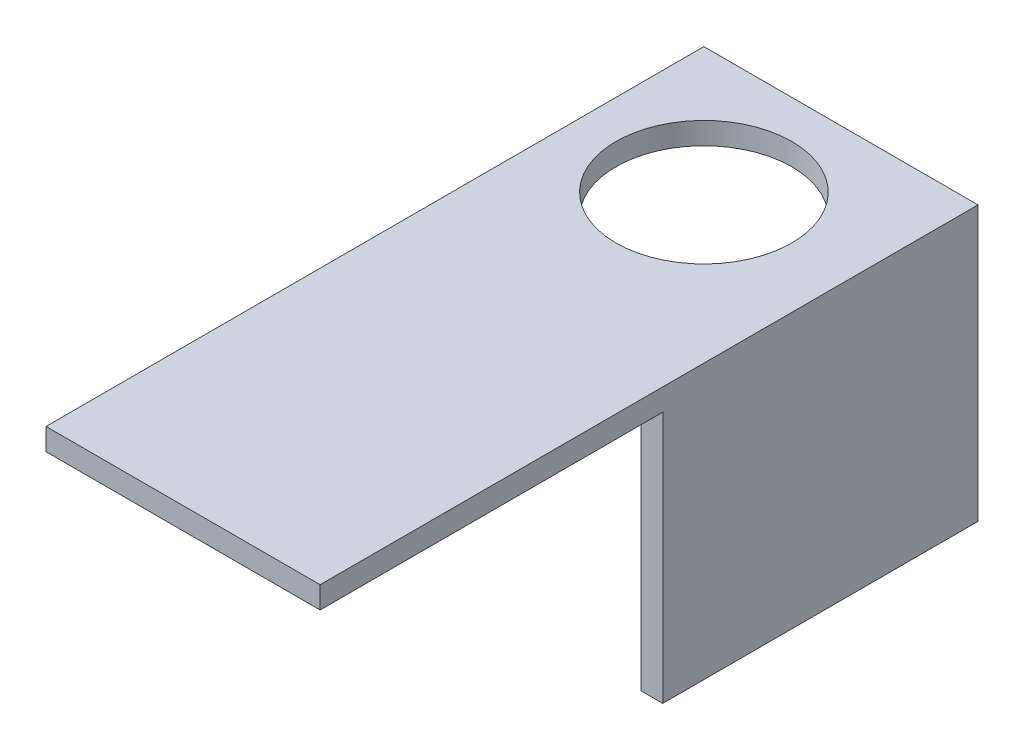
SolidWorks part; units mm, degrees
ref_plane "Alzado" through (0, 0, 0) normal (0, 0, 1) x (1, 0, 0)
ref_plane "Planta" through (0, 0, 0) normal (0, 1, 0) x (1, 0, 0)
ref_plane "Vista lateral" through (0, 0, 0) normal (1, 0, 0) x (0, 0, -1)
sketch "Croquis1" plane through (0, 0, 0) normal (0, 0, 1) x (1, 0, 0)
  line L0 (-124.6107, 44.964) -> (-74.6107, 44.964)
  line L1 (-74.6107, 44.964) -> (-74.6107, -5.036)
  line L2 (-124.6107, 44.964) -> (-124.6107, 40.964)
  line L3 (-124.6107, 40.964) -> (-78.6107, 40.964)
  line L4 (-78.6107, 40.964) -> (-78.6107, -5.036)
  line L5 (-78.6107, -5.036) -> (-74.6107, -5.036)
  dimension "D1" = 50
  dimension "D2" = 50
  dimension "D3" = 4
  dimension "D4" = 4
extrude "Saliente-Extruir1" add sketch "Croquis1" along normal blind 120
sketch "Croquis3" plane through (-78.6107, 0, 0) normal (-1, 0, 0) x (0, 0, 1)
  line L0 (120, 40.964) -> (57.5, 40.964)
  line L1 (120, 40.964) -> (0, 40.964) construction
  line L2 (57.5, 40.964) -> (57.5, -5.036)
  line L3 (120, -5.036) -> (0, -5.036) construction
  line L4 (57.5, -5.036) -> (120, -5.036)
  line L5 (120, -5.036) -> (120, 40.964)
  dimension "D1" = 62.5
extrude "Cortar-Extruir5" cut sketch "Croquis3" along normal blind 56 and the other way blind 35
sketch "Croquis4" plane through (0, 40.964, 0) normal (0, -1, 0) x (1, 0, 0)
  line L0 (-124.6107, 120) -> (-124.6107, 0) construction
  line L1 (-124.6107, 0) -> (-78.6107, 0) construction
  circle A0 centre (-101.6107, 23) radius 16.0398
  dimension "D1" = 23
  dimension "D2" = 23
extrude "Cortar-Extruir6" cut sketch "Croquis4" along normal blind 40 and the other way blind 42
